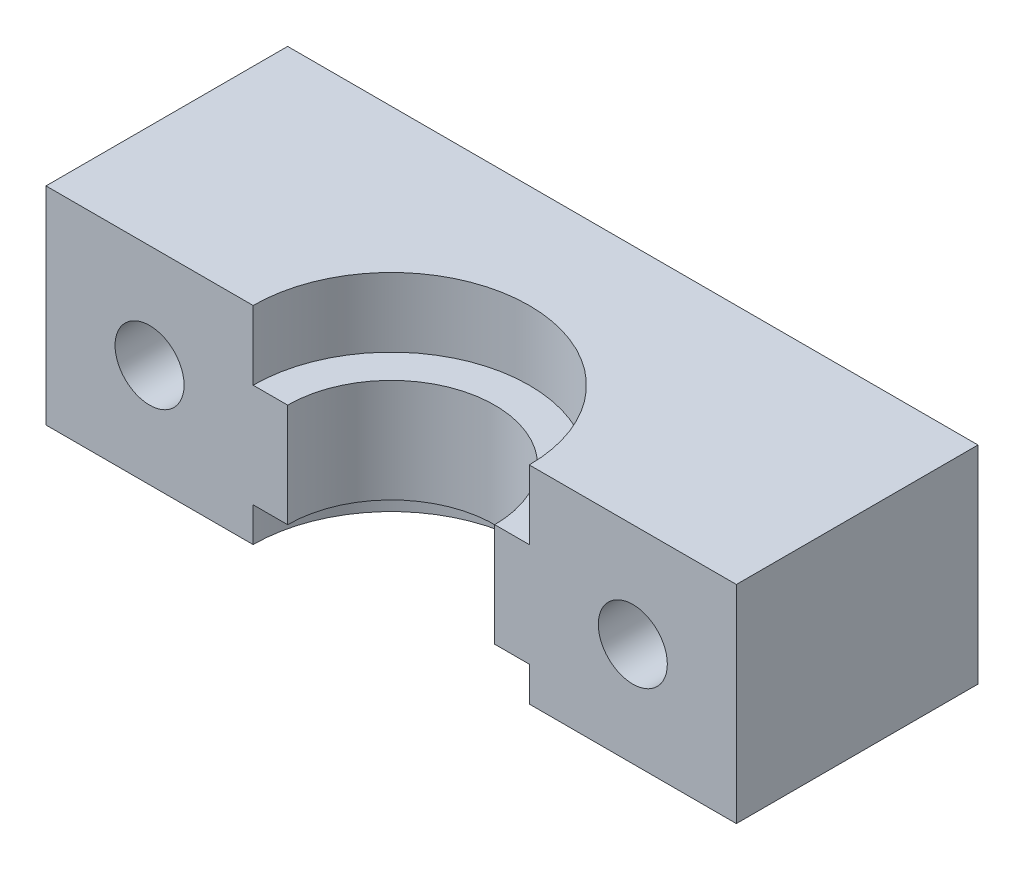
SolidWorks part; units mm, degrees
material "PLA"
ref_plane "Front Plane" through (0, 0, 0) normal (0, 0, 1) x (1, 0, 0)
ref_plane "Top Plane" through (0, 0, 0) normal (0, 1, 0) x (1, 0, 0)
ref_plane "Right Plane" through (0, 0, 0) normal (1, 0, 0) x (0, 0, -1)
sketch "Sketch1" plane through (0, 0, 0) normal (0, 0, 1) x (1, 0, 0)
  line L0 (47.1196, 22.4075) -> (47.1196, 10.4075) construction
  line L1 (7.1196, 10.4075) -> (47.1196, 10.4075)
  line L2 (7.1196, 10.4075) -> (7.1196, 22.4075)
  line L3 (7.1196, 22.4075) -> (47.1196, 22.4075)
  line L4 (47.1196, 10.4075) -> (47.1196, 22.4075)
  line L5 (35.1196, 22.4075) -> (47.1196, 22.4075) construction
  line L6 (47.1196, 10.4075) -> (35.1196, 10.4075) construction
  line L7 (7.1196, 22.4075) -> (7.1196, 12.4075) construction
  circle A0 centre (13.1196, 16.4075) radius 2
  circle A1 centre (41.1196, 16.4075) radius 2
  dimension "D1" = 4
extrude "Boss-Extrude1" add sketch "Sketch1" along normal blind 14
sketch "Sketch2" plane through (0, 0, 0) normal (0, 0, 1) x (1, 0, 0)
  circle A0 centre (13.1196, 16.4075) radius 3.5
  circle A1 centre (41.1196, 16.4075) radius 3.5
  dimension "D1" = 7
  dimension "D2" = 7
extrude "Cut-Extrude1" cut sketch "Sketch2" along normal blind 5
sketch "Sketch3" plane through (0, 0, 14) normal (0, 0, 1) x (1, 0, 0)
  line L0 (27.1196, 22.4075) -> (27.1196, 10.4075) construction
  line L1 (47.1196, 22.4075) -> (7.1196, 22.4075) construction
  line L2 (7.1196, 10.4075) -> (47.1196, 10.4075) construction
  line L3 (35.1196, 22.4075) -> (35.1196, 18.4075)
  line L4 (35.1196, 18.4075) -> (33.1196, 18.4075)
  line L5 (33.1196, 18.4075) -> (33.1196, 12.4075)
  line L6 (33.1196, 12.4075) -> (35.1196, 12.4075)
  line L7 (35.1196, 12.4075) -> (35.1196, 10.4075)
  line L8 (35.1196, 10.4075) -> (27.1196, 10.4075)
  line L9 (27.1196, 10.4075) -> (27.1196, 22.4075)
  line L10 (27.1196, 22.4075) -> (35.1196, 22.4075)
  dimension "D1" = 4
  dimension "D2" = 2
  dimension "D3" = 8
  dimension "D4" = 6
revolve "Cut-Revolve1" cut sketch "Sketch3" angle 360 about L0
